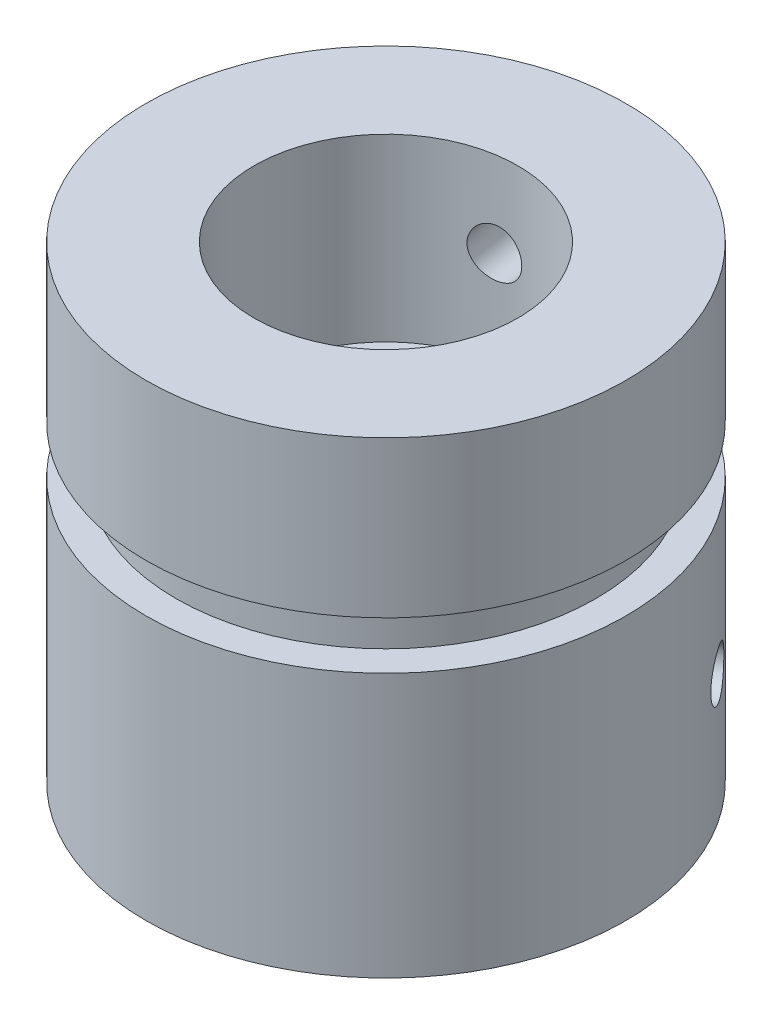
SolidWorks part; units mm, degrees
ref_plane "Front Plane" through (0, 0, 0) normal (0, 0, 1) x (1, 0, 0)
ref_plane "Top Plane" through (0, 0, 0) normal (0, 1, 0) x (1, 0, 0)
ref_plane "Right Plane" through (0, 0, 0) normal (1, 0, 0) x (0, 0, -1)
sketch "Sketch1" plane through (0, 0, 0) normal (0, 1, 0) x (1, 0, 0)
  circle A0 centre (0, 0) radius 20
  circle A1 centre (0, 0) radius 4
  dimension "D1" = 40
  dimension "D2" = 8
extrude "Boss-Extrude1" add sketch "Sketch1" along normal blind 22
sketch "Sketch2" plane through (0, 22, 0) normal (0, 1, 0) x (1, 0, 0)
  circle A0 centre (0, 0) radius 4
  circle A1 centre (0, 0) radius 17.5
  dimension "D1" = 35
extrude "Boss-Extrude2" add sketch "Sketch2" along normal blind 2
sketch "Sketch3" plane through (0, 24, 0) normal (0, 1, 0) x (1, 0, 0)
  circle A0 centre (0, 0) radius 17.5
  circle A1 centre (0, 0) radius 11
  dimension "D1" = 22
extrude "Boss-Extrude3" add sketch "Sketch3" along normal blind 2
sketch "Sketch4" plane through (0, 26, 0) normal (0, 1, 0) x (1, 0, 0)
  circle A0 centre (0, 0) radius 11
  circle A1 centre (0, 0) radius 20
extrude "Boss-Extrude4" add sketch "Sketch4" along normal blind 13
hole_wizard "Ø4.0 (4) Diameter Hole1" positions "3DSketch1" profile "Sketch5" hole size "Ø4.0" standard "ANSI Metric"
sketch3d "3DSketch1"
  point P0 (16.591, 10.5326, -11.1687)
sketch "Sketch5" plane through (16.591, 10.5326, -11.1687) normal (0, 1, 0) x (-0.5584, 0, -0.8295)
  line L0 (0, 0) -> (0, 16)
  line L1 (0, 16) -> (2, 16)
  line L2 (2, 16) -> (2, 0)
  line L5 (2, 0) -> (0, 0)
  line L11 (0, -6.35) -> (0, 107.95) construction
  dimension "Thru Hole Dia." = 4
  dimension "Thru Hole Depth" = 16
hole_wizard "Ø4.0 (4) Diameter Hole2" positions "3DSketch2" profile "Sketch6" hole size "Ø4.0" standard "ANSI Metric"
sketch3d "3DSketch2"
  point P0 (-3.0525, 31.9184, -19.7657)
sketch "Sketch6" plane through (-3.0525, 31.9184, -19.7657) normal (0, 1, 0) x (-0.9883, 0, 0.1526)
  line L0 (0, 0) -> (0, 9)
  line L1 (0, 9) -> (2, 9)
  line L2 (2, 9) -> (2, 0)
  line L5 (2, 0) -> (0, 0)
  line L11 (0, -6.35) -> (0, 107.95) construction
  dimension "Thru Hole Dia." = 4
  dimension "Thru Hole Depth" = 9
